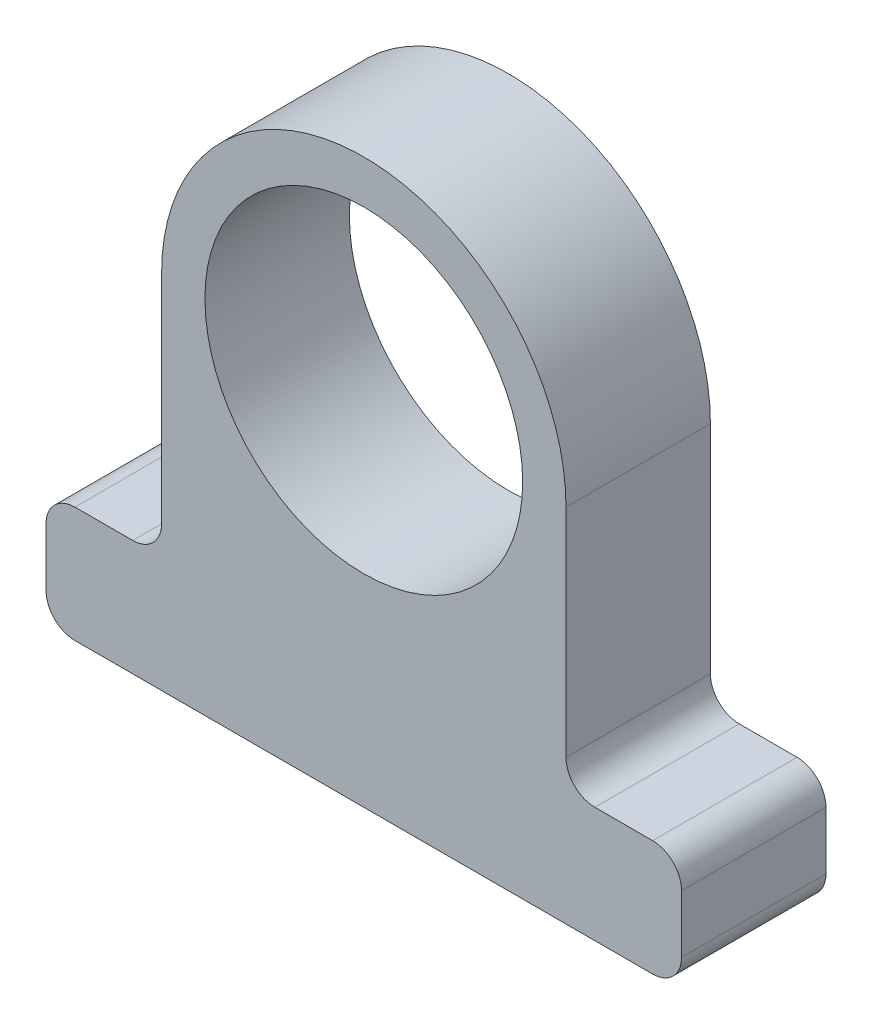
SolidWorks part; units mm, degrees
ref_plane "Front Plane" through (0, 0, 0) normal (0, 0, 1) x (1, 0, 0)
ref_plane "Top Plane" through (0, 0, 0) normal (0, 1, 0) x (1, 0, 0)
ref_plane "Right Plane" through (0, 0, 0) normal (1, 0, 0) x (0, 0, -1)
sketch "Sketch1" plane through (0, 0, 0) normal (0, 0, 1) x (1, 0, 0)
  line L0 (-14, 0) -> (-14, -17)
  line L1 (-14, -17) -> (-22, -17)
  line L2 (-22, -17) -> (-22, -25)
  line L3 (-22, -25) -> (22, -25)
  line L4 (22, -25) -> (22, -17)
  line L5 (22, -17) -> (14, -17)
  line L6 (14, -17) -> (14, 0)
  circle A0 centre (0, 0) radius 14
  circle A1 centre (0, 0) radius 11
  dimension "D1" = 22
  dimension "D2" = 28
  dimension "D3" = 25
  dimension "D4" = 8
  dimension "D5" = 8
extrude "Boss-Extrude1" add sketch "Sketch1" along normal blind 10 contours A0 L0 L1 L2 L3 L4 L5 L6 | A0 A1
fillet "Fillet1" radius 2 6 edges at (-22, -25, 5) (-14, -17, 5) (-22, -17, 5) (22, -25, 5) (22, -17, 5) (14, -17, 5)
